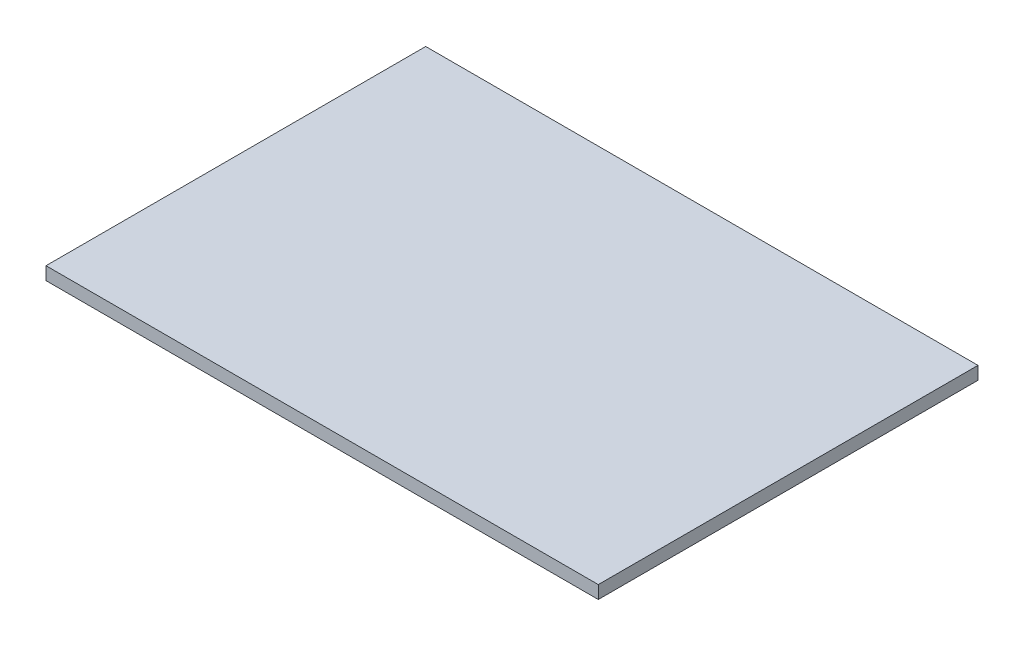
SolidWorks part; units mm, degrees
material "Pine"
ref_plane "Front Plane" through (0, 0, 0) normal (0, 0, 1) x (1, 0, 0)
ref_plane "Top Plane" through (0, 0, 0) normal (0, 1, 0) x (1, 0, 0)
ref_plane "Right Plane" through (0, 0, 0) normal (1, 0, 0) x (0, 0, -1)
sketch "Sketch1" plane through (0, 0, 0) normal (0, 1, 0) x (1, 0, 0)
  line L0 (-539.4098, 0) -> (273.3902, 0)
  line L1 (273.3902, 0) -> (273.3902, 558.8)
  line L2 (273.3902, 558.8) -> (-539.4098, 558.8)
  line L3 (-539.4098, 558.8) -> (-539.4098, 0)
extrude "Boss-Extrude1" add sketch "Sketch1" along normal blind 19.05
